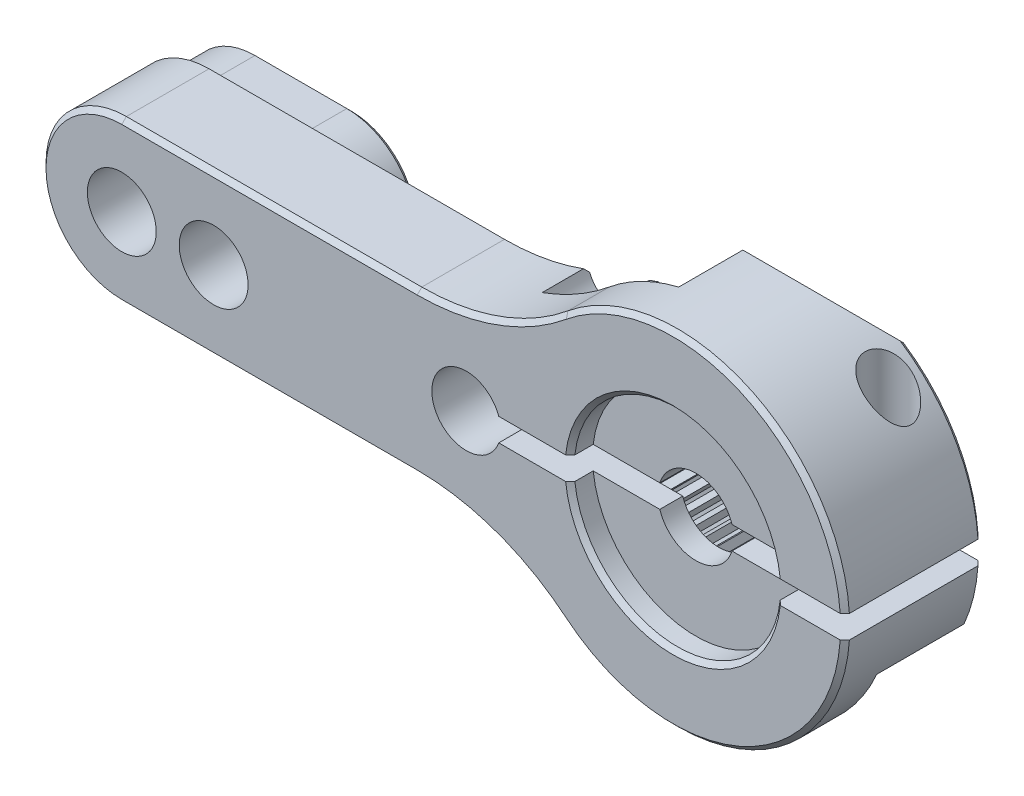
SolidWorks part; units mm, degrees
ref_plane "Plan de face" through (0, 0, 0) normal (0, 0, 1) x (1, 0, 0)
ref_plane "Plan de dessus" through (0, 0, 0) normal (0, 1, 0) x (1, 0, 0)
ref_plane "Plan de droite" through (0, 0, 0) normal (1, 0, 0) x (0, 0, -1)
sketch "Esquisse1" plane through (0, 0, 0) normal (0, 0, 1) x (1, 0, 0)
  line L0 (-11.1355, 3.5) -> (-24, 3.5)
  line L1 (-24, -3.5) -> (-11.1355, -3.5)
  line L2 (0, 0) -> (-40.4273, 0) construction
  line L3 (-27.5, 8.0474) -> (-27.5, -5.9021) construction
  line L4 (7.5, 11.0169) -> (7.5, -8.8025) construction
  circle A1 centre (0, 0) radius 1.65
  arc A2 (-4.7724, 5.7857) -> (-4.7724, -5.7857) centre (0, 0) cw
  arc A3 (-24, 3.5) -> (-24, -3.5) centre (-24, 0) ccw
  arc A4 (-11.1355, -3.5) -> (-4.7724, -5.7857) centre (-11.1355, -13.5) cw
  arc A5 (-4.7724, 5.7857) -> (-11.1355, 3.5) centre (-11.1355, 13.5) cw
  circle A6 centre (-9, 0) radius 1.5
  circle A7 centre (-24, 0) radius 1.5
  circle A8 centre (-20, 0) radius 1.5
  point P14 (-6.6332, -3.5)
  point P18 (-6.6332, 3.5)
  dimension "D1" = 7.5
  dimension "D2" = 3.3
  dimension "D5" = 10
  dimension "D6" = 3
  dimension "D7" = 3
  dimension "D8" = 3
  dimension "D3" = 7
  dimension "D4" = 35
  dimension "D9" = 9
  dimension "D10" = 11
  dimension "D11" = 4
extrude "Boss.-Extru.1" add sketch "Esquisse1" along normal blind 6
sketch "Esquisse2" plane through (0, 0, 6) normal (0, 0, 1) x (1, 0, 0)
  line L0 (7.5, 0) -> (-41.9387, 0) construction
  line L1 (8.5, 0.5) -> (-10.4142, 0.5)
  line L2 (8.5, 0.5) -> (8.5, -0.5)
  line L3 (8.5, -0.5) -> (-10.4142, -0.5)
  line L4 (-10.4142, 0.5) -> (-10.4142, -0.5)
  arc A0 (-4.7724, -5.7857) -> (-4.7724, 5.7857) centre (0, 0) ccw construction
  circle A1 centre (-9, 0) radius 1.5 construction
  dimension "D1" = 1
  dimension "D2" = 1
extrude "Enlèv. mat.-Extru.1" cut sketch "Esquisse2" against normal blind 6
sketch "Esquisse3" plane through (0, 0, 0) normal (0, 0, -1) x (-1, 0, 0)
  line L2 (24, -3.5) -> (11.1355, -3.5)
  line L3 (24, -3.5) -> (11.1355, -3.5)
  line L5 (24, 0) -> (20, 0) construction
  line L6 (11.1355, 3.5) -> (24, 3.5)
  line L7 (11.1355, 3.5) -> (24, 3.5)
  line L8 (24, -3) -> (20, -3)
  line L9 (24, 3) -> (20, 3)
  arc A0 (4.7724, 5.7857) -> (4.7724, -5.7857) centre (0, 0) cw
  arc A5 (11.1355, -3.5) -> (4.7724, -5.7857) centre (11.1355, -13.5) ccw
  arc A6 (11.1355, -3.5) -> (4.7724, -5.7857) centre (11.1355, -13.5) ccw
  arc A10 (24, -3) -> (24, 3) centre (24, 0) ccw
  arc A11 (20, 3) -> (20, -3) centre (20, 0) ccw
  arc A12 (24, -3.5) -> (24, 3.5) centre (24, 0) ccw
  arc A13 (4.7724, 5.7857) -> (11.1355, 3.5) centre (11.1355, 13.5) ccw
  arc A14 (24, -3.5) -> (24, 3.5) centre (24, 0) ccw
  arc A15 (4.7724, 5.7857) -> (11.1355, 3.5) centre (11.1355, 13.5) ccw
  point P5 (22, 0)
  dimension "D3" = 4
  dimension "D4" = 0.5
  dimension "D1" = 0
  dimension "D2" = 0
extrude "Enlèv. mat.-Extru.2" cut sketch "Esquisse3" against normal blind 2
sketch "Esquisse4" plane through (0, 0, 0) normal (0, 0, -1) x (-1, 0, 0)
  line L0 (-7.5, -3) -> (-3.25, -3)
  line L1 (-1.75, -4.5) -> (-1.75, -7.5)
  line L2 (-1.75, -7.5) -> (-7.5, -7.5)
  line L3 (-7.5, -7.5) -> (-7.5, -3)
  line L4 (-1.5724, -0.5) -> (-7.4833, -0.5) construction
  line L5 (1.5724, 0.5) -> (7.4833, 0.5) construction
  line L6 (1.75, 7.5) -> (7.75, 7.5)
  line L7 (1.75, 7.5) -> (1.75, 4.5)
  line L8 (3.25, 3) -> (6.25, 3)
  line L9 (7.75, 7.5) -> (7.75, 4.5)
  arc A0 (7.4833, 0.5) -> (-7.4833, 0.5) centre (0, 0) ccw construction
  arc A1 (-7.4833, -0.5) -> (7.4833, -0.5) centre (0, 0) ccw construction
  arc A2 (-3.25, -3) -> (-1.75, -4.5) centre (-3.25, -4.5) cw
  arc A3 (6.25, 3) -> (7.75, 4.5) centre (6.25, 4.5) ccw
  arc A4 (1.75, 4.5) -> (3.25, 3) centre (3.25, 4.5) ccw
  point P14 (-1.75, -3)
  dimension "D3" = 1.5
  dimension "D7" = 1.5
  dimension "D1" = 5.75
  dimension "D2" = 2.5
  dimension "D4" = 3.5
  dimension "D5" = 2.5
  dimension "D6" = 6
extrude "Enlèv. mat.-Extru.3" cut sketch "Esquisse4" against normal blind 4
sketch "Esquisse5" plane through (0, -3, 0) normal (0, -1, 0) x (1, 0, 0)
  line L0 (3.25, 4) -> (6.8739, 4) construction
  line L2 (6.8739, 4) -> (6.8739, 0) construction
  circle A0 centre (4.8739, 1.5) radius 1
  dimension "D1" = 2
  dimension "D2" = 2.5
  dimension "D3" = 2
extrude "Enlèv. mat.-Extru.4" cut sketch "Esquisse5" against normal through all
sketch "Esquisse6" plane through (0, 3, 0) normal (0, 1, 0) x (1, 0, 0)
  line L0 (-7.4833, -2) -> (-7.4833, 0) construction
  line L1 (4.8739, -1.5) -> (-10.9129, -1.5) construction
  circle A0 centre (-5.2333, -1.5) radius 1
  dimension "D1" = 2
  dimension "D2" = 2.25
extrude "Enlèv. mat.-Extru.5" cut sketch "Esquisse6" against normal through all
sketch "Esquisse7" plane through (0, 0, 0) normal (1, 0, 0) x (0, 0, -1)
  line L0 (-1.4142, 7.5) -> (0, 6.0858)
  line L1 (0, 7.5) -> (-6, 7.5) construction
  line L2 (0, 0.5) -> (0, 7.5) construction
  line L3 (0, 6.0858) -> (0, 7.5)
  line L4 (0, 7.5) -> (-1.4142, 7.5)
  line L5 (0, -6.0858) -> (-1.4142, -7.5)
  line L6 (0, -7.293) -> (0, -4.5) construction
  line L7 (-1.4142, -7.5) -> (0, -7.5)
  line L8 (0, -7.5) -> (0, -6.0858)
  line L9 (0, -7.5) -> (0, -0.5) construction
  dimension "D1" = 2
  dimension "D2" = 45
  dimension "D3" = 45
  dimension "D4" = 2
  dimension "D5" = 15
extrude "Enlèv. mat.-Extru.6" cut sketch "Esquisse7" against normal blind 10 and the other way blind 10
sketch "Esquisse8" plane through (0, 0, 0) normal (0, 0, -1) x (-1, 0, 0)
  circle A0 centre (0, 0) radius 3
  dimension "D1" = 6
extrude "Enlèv. mat.-Extru.7" cut sketch "Esquisse8" against normal blind 4
sketch "Esquisse9" plane through (0, 0, 0) normal (0, 0, -1) x (-1, 0, 0)
  line L0 (0, 0) -> (0, 3.5855) construction
  line L1 (-0.8887, 3) -> (1.1976, 3) construction
  line L2 (-0.2021, 3) -> (0, 2.65)
  line L3 (0, 2.65) -> (0.2021, 3)
  line L4 (0.2021, 3) -> (-0.2021, 3)
  arc A0 (2.958, 0.5) -> (-2.958, 0.5) centre (0, 0) ccw construction
  dimension "D1" = 30
  dimension "D2" = 0.35
extrude "Boss.-Extru.2" add sketch "Esquisse9" against normal up to surface (4 mm away) up to face at (0, 1.4125, 4)
pattern_circular "Répétition circulaire1" count 36 over 360 about axis through (0, 0, 0) along (0, 0, 1) skipping 9, 27 of "Boss.-Extru.2"
sketch "Esquisse10" plane through (0, 0, 0) normal (0, 0, -1) x (-1, 0, 0)
  line L0 (7.4833, -0.5) -> (2.9581, -0.5) construction
  line L1 (-7.4833, 0.5) -> (3.8917, 0.5)
  line L2 (-7.4833, 0.5) -> (-7.4833, -0.5)
  line L3 (-7.4833, -0.5) -> (3.8917, -0.5)
  line L4 (3.8917, 0.5) -> (3.8917, -0.5)
extrude "Enlèv. mat.-Extru.8" cut sketch "Esquisse10" against normal through all
chamfer "Chanfrein1" distance 0.2 angle 45 22 edges at (-17.5678, -3.5, 2) (-27, 0, 0) (-17, 0, 0) (-22, 3, 0) (-7.2716, 1.8368, 0) (-7.7549, -4.0888, 6) (7.2866, -1.7763, 0) (2.9702, -6.8868, 6) (-8.5271, -3.8462, 2) (-5.6206, -5.1582, 2.422) (-7.7549, 4.0888, 6) (-17.5678, 3.5, 6) (6.5578, 3.6395, 0) (2.9702, 6.8868, 6) (-27.5, 0, 6) (-6.5578, -3.6395, 0) (-17.5678, -3.5, 6) (-9.3901, 3.6535, 2) (-17.5678, 3.5, 2) (-27.5, 0, 2)
sketch "Esquisse11" plane through (0, 0, 6) normal (0, 0, 1) x (1, 0, 0)
  circle A0 centre (0, 0) radius 4.5
  dimension "D1" = 9
extrude "Enlèv. mat.-Extru.9" cut sketch "Esquisse11" against normal blind 1
chamfer "Chanfrein2" distance 0.2 angle 45 2 edges at (0, -4.5, 6) (0, 4.5, 6)
